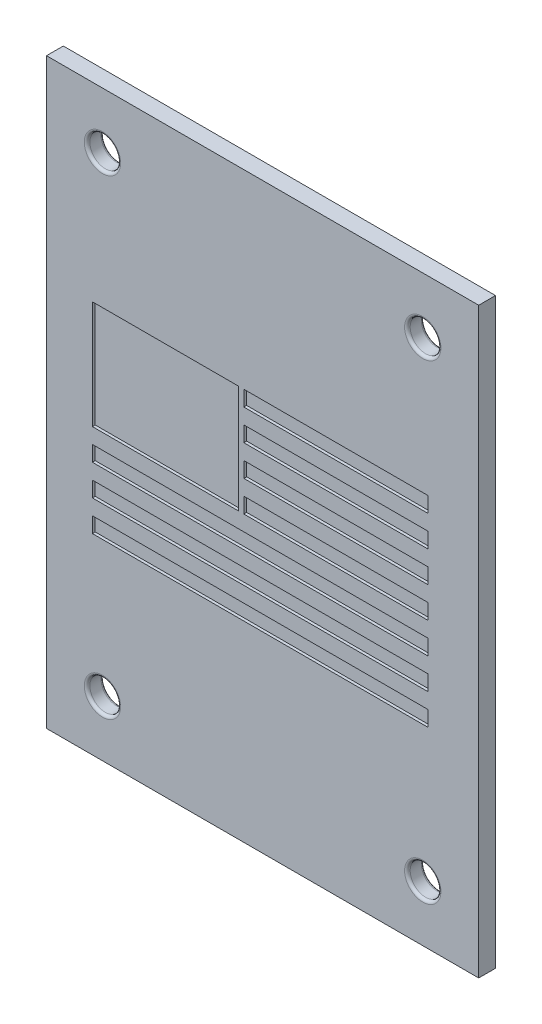
SolidWorks part; units mm, degrees
ref_plane "Front Plane" through (0, 0, 0) normal (0, 0, 1) x (1, 0, 0)
ref_plane "Top Plane" through (0, 0, 0) normal (0, 1, 0) x (1, 0, 0)
ref_plane "Right Plane" through (0, 0, 0) normal (1, 0, 0) x (0, 0, -1)
sketch "Sketch1" plane through (0, 0, 0) normal (0, 0, 1) x (1, 0, 0)
  line L1 (-38.625, -52.07) -> (38.625, -52.07)
  line L2 (-38.625, -52.07) -> (-38.625, 52.07)
  line L3 (-38.625, 52.07) -> (38.625, 52.07)
  line L4 (38.625, -52.07) -> (38.625, 52.07)
  line L5 (-38.625, -52.07) -> (38.625, 52.07) construction
  line L6 (-38.625, 52.07) -> (38.625, -52.07) construction
  point P0 (0, 0)
  dimension "D1" = 77.25
  dimension "D2" = 104.14
extrude "Boss-Extrude1" add sketch "Sketch1" along normal blind 3
sketch "Sketch2" plane through (0, 0, 3) normal (0, 0, 1) x (1, 0, 0)
  line L0 (38.625, 52.07) -> (-38.625, 52.07) construction
  line L1 (-38.625, 52.07) -> (-38.625, -52.07) construction
  line L2 (0, 0) -> (0, 50000) construction
  line L3 (0, 0) -> (50000, 0) construction
  circle A0 centre (-28.625, 42.07) radius 2.75
  circle A1 centre (28.625, 42.07) radius 2.75
  circle A2 centre (28.625, -42.07) radius 2.75
  circle A3 centre (-28.625, -42.07) radius 2.75
  dimension "D1" = 10
  dimension "D3" = 5.5
  dimension "D2" = 10
extrude "Cut-Extrude1" cut sketch "Sketch2" against normal through all
sketch "Sketch3" [suppressed] plane through (0, 0, 3) normal (0, 0, 1) x (1, 0, 0)
  text T1 "<b>  School of </b>\r\n<b>Engineering</b>\r\n<b>Technology</b>" font "Century Gothic" height in points 48
extrude "Cut-Extrude2" [suppressed] cut sketch "Sketch3" against normal blind 0.5
sketch "Sketch5" plane through (0, 0, 3) normal (0, 0, 1) x (1, 0, 0)
  line L0 (-9.7309, 10.0231) -> (-15.5666, -6.0101)
  line L1 (-15.5666, -6.0101) -> (-22.7346, -6.0101)
  line L2 (-22.7346, -6.0101) -> (-25.4708, -13.5277)
  line L3 (-25.4708, -13.5277) -> (-1.3321, -13.5277)
  line L4 (-1.3321, -13.5277) -> (1.4041, -6.0101)
  line L5 (1.4041, -6.0101) -> (-2.2976, -6.0101)
  line L6 (-2.2976, -6.0101) -> (-1.2716, -3.1911)
  line L7 (-1.2716, -3.1911) -> (15.0107, -3.1911)
  line L8 (-11.7357, 17.5407) -> (15.0107, 17.5407)
  line L9 (-16.899, 10.0231) -> (-9.7309, 10.0231)
  line L10 (-16.899, 10.0231) -> (-14.1628, 17.5407)
  line L11 (-14.1628, 17.5407) -> (-11.7357, 17.5407)
  line L12 (1.8173, 5.2954) -> (3.1853, 9.0542)
  line L13 (3.1853, 9.0542) -> (15.0107, 9.0542)
  line L14 (1.8173, 5.2954) -> (15.0107, 5.2954)
  line L15 (-12.5872, 8.0231) -> (-16.967, -4.0101)
  line L16 (-16.967, -4.0101) -> (-24.1351, -4.0101)
  line L17 (-24.1351, -4.0101) -> (-28.3271, -15.5277)
  line L18 (-28.3271, -15.5277) -> (0.0683, -15.5277)
  line L19 (-11.7357, 19.5407) -> (15.0107, 19.5407)
  line L20 (-15.5633, 19.5407) -> (-11.7357, 19.5407)
  line L21 (-19.7553, 8.0231) -> (-15.5633, 19.5407)
  line L22 (-19.7553, 8.0231) -> (-12.5872, 8.0231)
  line L24 (0.0683, -15.5277) -> (3.8305, -5.1911)
  line L26 (3.8305, -5.1911) -> (15.0107, -5.1911)
  arc A0 (15.0107, 17.5407) -> (15.0107, -3.1911) centre (15.0107, 7.1748) cw
  arc A1 (15.0107, 9.0542) -> (15.0107, 5.2954) centre (15.0107, 7.1748) cw
  arc A2 (15.0107, 19.5407) -> (15.0107, -5.1911) centre (15.0107, 7.1748) cw
  point P2 (2.5013, 7.1748)
  dimension "D1" = 3
  dimension "D2" = 4
extrude "Cut-Extrude4" [suppressed] cut sketch "Sketch5" against normal blind 0.5 contours A1 L13 L12 L14 | A2 L19 L20 L21 L22 L15 L16 L17 L18 L24 L26 L8 A0 L7 L6 L5 L4 L3 L2 L1 L0 L9 L10 L11
sketch "Sketch7" plane through (0, 0, 3) normal (0, 0, 1) x (1, 0, 0)
  line L6 (-30.4289, 18.0795) -> (-30.4289, -17.8005)
  line L9 (29.5711, 18.0795) -> (-30.4289, 18.0795)
  line L10 (29.7809, 15.3195) -> (-3.3534, 15.3195)
  line L12 (29.5711, 18.0795) -> (29.5711, -17.8005)
  line L13 (29.7809, 12.5595) -> (-3.3534, 12.5595)
  line L14 (29.7809, 9.7995) -> (-3.3534, 9.7995)
  line L16 (29.7809, 7.0395) -> (-3.3534, 7.0395)
  line L580 (29.7809, 4.2795) -> (-3.3534, 4.2795)
  line L581 (29.7809, 1.5195) -> (-3.3534, 1.5195)
  line L582 (29.5711, -1.2405) -> (-30.4289, -1.2405)
  line L584 (29.5711, -4.0005) -> (-30.4289, -4.0005)
  line L1148 (29.5711, -6.7605) -> (-30.4289, -6.7605)
  line L1149 (29.5711, -9.5205) -> (-30.4289, -9.5205)
  line L1150 (29.5711, -12.2805) -> (-30.4289, -12.2805)
  line L1151 (-30.4289, -1.2405) -> (-30.4289, 18.0795)
  line L1152 (29.5711, -15.0405) -> (-30.4289, -15.0405)
  line L1153 (29.5711, -17.8005) -> (-30.4289, -17.8005)
  line L1154 (-30.4289, -1.2405) -> (-4.3534, -1.2405)
  line L1155 (-4.3534, 1.5195) -> (-4.3534, 4.2795)
  line L1156 (-30.4289, 18.0795) -> (-4.3534, 18.0795)
  line L1729 (-4.3534, 12.5595) -> (-4.3534, 15.3195)
  line L1730 (-4.3534, 7.0395) -> (-4.3534, 9.7995)
  line L1731 (-4.3534, 18.0795) -> (-4.3534, -1.2405)
  line L1732 (-3.3534, 18.0795) -> (-3.3534, -1.2405)
  dimension "D1" = 1
extrude "Cut-Extrude7" cut sketch "Sketch7" against normal blind 0.5
sketch "Sketch8" [suppressed] plane through (0, 0, 3) normal (0, 0, 1) x (1, 0, 0)
  text T0 "<b>    Purdue</b>\r\n<b>Polytechnic</b>\r\n<b>    Institute</b>" font "Century Gothic" height in points 48
extrude "Cut-Extrude8" [suppressed] cut sketch "Sketch8" against normal blind 0.5
fillet "Fillet1" radius 0.5 8 edges at (25.875, 42.07, 3) (25.875, 42.07, 0) (31.375, -42.07, 3) (31.375, -42.07, 0) (-31.375, -42.07, 3) (-31.375, -42.07, 0) (-25.875, 42.07, 3) (-25.875, 42.07, 0)
